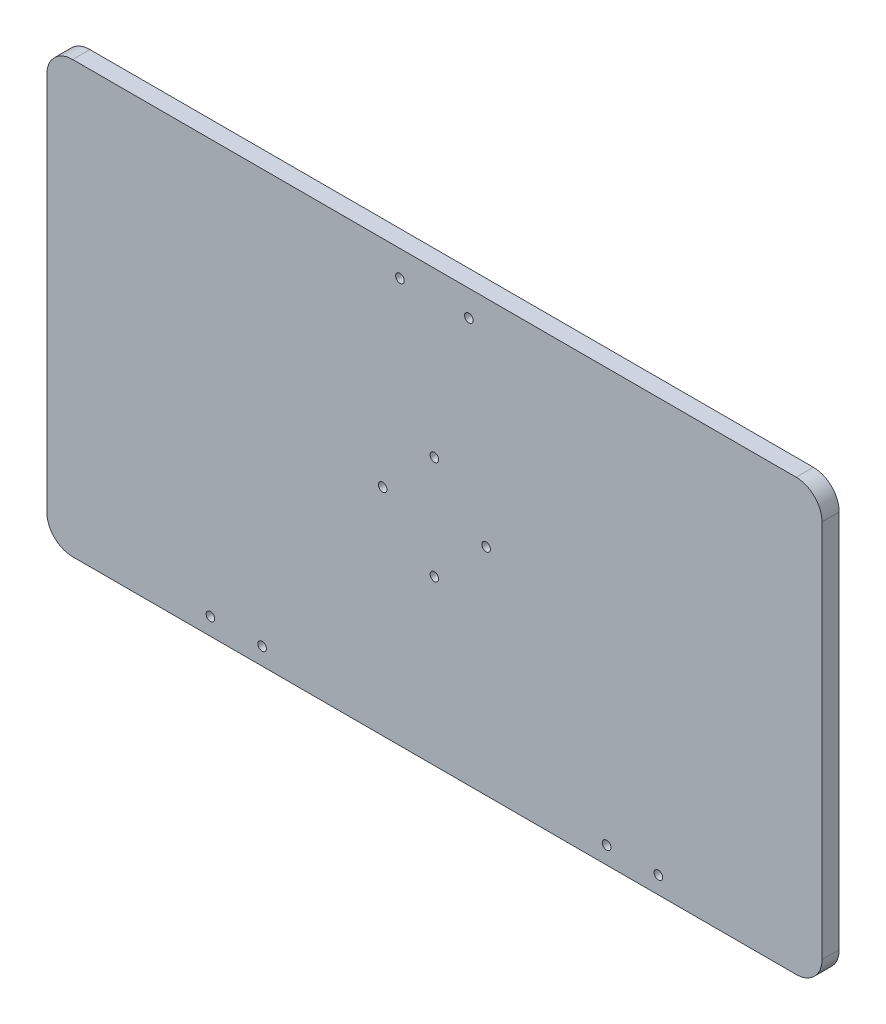
SolidWorks part; units mm, degrees
ref_plane "Alzado" through (0, 0, 0) normal (0, 0, 1) x (1, 0, 0)
ref_plane "Planta" through (0, 0, 0) normal (0, 1, 0) x (1, 0, 0)
ref_plane "Vista lateral" through (0, 0, 0) normal (1, 0, 0) x (0, 0, -1)
sketch "Croquis1" plane through (0, 0, 0) normal (0, 0, 1) x (1, 0, 0)
  line L0 (415, 125) -> (450, 125) construction
  line L1 (15, 0) -> (435, 0)
  line L2 (0, 15) -> (0, 235)
  line L3 (15, 250) -> (435, 250)
  line L4 (450, 15) -> (450, 235)
  line L9 (110, 250) -> (110, 0) construction
  line L10 (135, 10) -> (125, 10) construction
  line L11 (135, 0) -> (85, 0) construction
  line L12 (135, 0) -> (135, 20) construction
  line L13 (135, 20) -> (85, 20) construction
  line L14 (85, 0) -> (85, 20) construction
  line L15 (125, 10) -> (95, 10) construction
  line L16 (225, 250) -> (225, 0) construction
  line L17 (0, 125) -> (450, 125) construction
  line L18 (95, 10) -> (85, 10) construction
  line L23 (245, 235) -> (205, 235) construction
  line L67 (315, 0) -> (325.0903, 0) construction
  arc A5 (435, 250) -> (450, 235) centre (435, 235) cw
  arc A6 (435, 0) -> (450, 15) centre (435, 15) ccw
  arc A7 (15, 0) -> (0, 15) centre (15, 15) cw
  arc A8 (0, 235) -> (15, 250) centre (15, 235) cw
  circle A28 centre (255, 125) radius 2.5
  circle A29 centre (225, 95) radius 2.5
  circle A30 centre (195, 125) radius 2.5
  circle A31 centre (225, 155) radius 2.5
  circle A32 centre (125, 10) radius 2.5
  circle A33 centre (95, 10) radius 2.5
  circle A34 centre (355, 10) radius 2.5
  circle A35 centre (325, 10) radius 2.5
  circle A36 centre (245, 235) radius 2.5
  circle A37 centre (205, 235) radius 2.5
  point P21 (110, 20)
  point P29 (450, 0)
  point P32 (0, 0)
  point P35 (0, 250)
  point P46 (225, 125)
  point P51 (225, 235)
  dimension "D5" = 4
  dimension "D8" = 50
  dimension "D9" = 5
  dimension "D10" = 15
  dimension "D11" = 20
  dimension "D13" = 5
  dimension "D3" = 5
  dimension "D1" = 450
  dimension "D2" = 250
  dimension "D4" = 30
  dimension "D6" = 110
  dimension "D7" = 30
  dimension "D12" = 40
  dimension "D14" = 15
extrude "Saliente-Extruir1" add sketch "Croquis1" along normal blind 10
